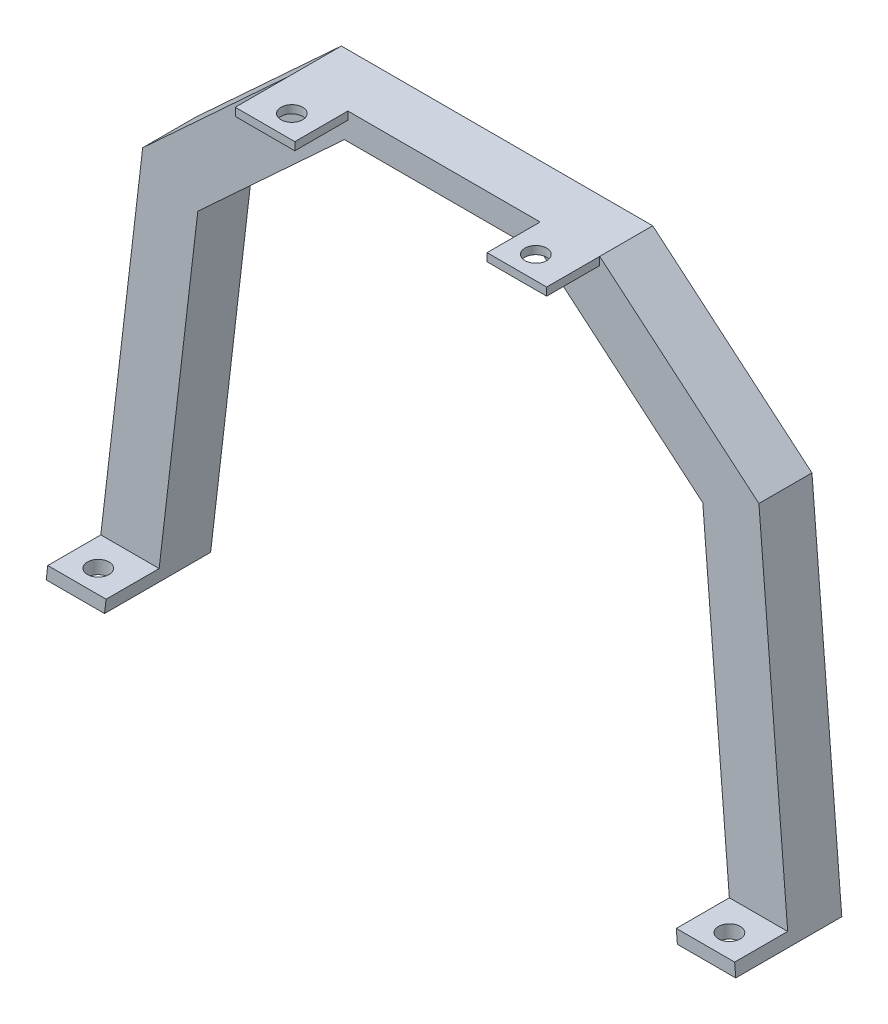
SolidWorks part; units mm, degrees
ref_plane "Front Plane" through (0, 0, 0) normal (0, 0, 1) x (1, 0, 0)
ref_plane "Top Plane" through (0, 0, 0) normal (0, 1, 0) x (1, 0, 0)
ref_plane "Right Plane" through (0, 0, 0) normal (1, 0, 0) x (0, 0, -1)
sketch "Sketch1" plane through (0, 0, 0) normal (0, 0, 1) x (1, 0, 0)
  line L0 (0, 0) -> (-11, 0)
  line L2 (108, 0) -> (119, 0)
  line L3 (-11, 0) -> (-2.811, 69.6627)
  line L16 (-2.811, 69.6627) -> (24.6463, 95)
  line L17 (24.6463, 95) -> (83.3537, 95)
  line L18 (83.3537, 95) -> (113.3741, 69.6627)
  line L19 (113.3741, 69.6627) -> (119, 0)
  line L20 (0, 0) -> (7.5811, 64.4912)
  line L21 (7.5811, 64.4912) -> (35.2243, 90)
  line L22 (35.2243, 90) -> (72.5681, 90)
  line L23 (72.5681, 90) -> (102.7918, 64.4912)
  line L24 (102.7918, 64.4912) -> (108, 0)
  point P1 (76.9939, 69.7206)
  point P3 (42.495, 69.6707)
  point P7 (0, 0)
  point P9 (0, 0)
  point P10 (4.4927, 54.3432)
  point P11 (0, 0)
  point P12 (29.0306, 74.7943)
  point P13 (1.953, 52.9858)
  point P14 (0, 0)
  point P15 (1.156, 51.9158)
  point P16 (110.4264, 51.9158)
  point P17 (110.0227, 51.9158)
  point P18 (-3.1434, 51.9158)
  point P25 (103.3774, 58.6554)
  point P26 (54, 95)
  point P27 (0, 0)
  point P29 (0, 0)
  point P30 (0, 0)
  point P31 (0, 0)
  point P32 (108, 69.1904)
  point P33 (98.6664, 62.6362)
  point P34 (81.8482, 93.6757)
  point P35 (76.1597, 90)
  point P36 (111.8984, 70.798)
  point P37 (-2.8611, 69.0667)
  point P38 (35.2271, 90)
  point P39 (72.2025, 90)
  point P40 (104.3549, 64.4912)
  point P41 (113.3823, 69.5614)
  dimension "D1" = 130
  dimension "D2" = 11
  dimension "D3" = 90
  dimension "D4" = 65
  dimension "D5" = 5
extrude "Boss-Extrude1" add sketch "Sketch1" along normal blind 10
sketch "Sketch2" plane through (0, 0, 10) normal (0, 0, 1) x (1, 0, 0)
  line L0 (-11, 0) -> (0, 0)
  line L1 (0, 0) -> (0.2939, 2.5)
  line L2 (0, 0) -> (7.5811, 64.4912) construction
  line L3 (0.2939, 2.5) -> (-10.7061, 2.5)
  line L4 (-2.811, 69.6627) -> (-11, 0) construction
  line L5 (-10.7061, 2.5) -> (-11, 0)
  line L6 (108, 0) -> (119, 0)
  line L7 (119, 0) -> (118.7981, 2.5)
  line L8 (119, 0) -> (113.3741, 69.6627) construction
  line L9 (118.7981, 2.5) -> (107.7981, 2.5)
  line L10 (102.7918, 64.4912) -> (108, 0) construction
  line L11 (107.7981, 2.5) -> (108, 0)
  point P14 (-5.5, 0)
  point P21 (113.5, 0)
  dimension "D1" = 2.5
  dimension "D2" = 2.5
extrude "Boss-Extrude2" add sketch "Sketch2" along normal blind 10
sketch "Sketch3" plane through (0, 2.5, 0) normal (0, 1, 0) x (1, 0, 0)
  line L0 (-11, -20) -> (-11, 0) construction
  line L1 (119, -20) -> (119, 0) construction
  circle A0 centre (-5.5, -15.6874) radius 2.05
  circle A1 centre (113.5, -15.6874) radius 2.05
  point P8 (0, 0)
  dimension "D3" = 4.1
  dimension "D1" = 5.5
  dimension "D2" = 5.5
extrude "Cut-Extrude1" cut sketch "Sketch3" against normal blind 10
sketch "Sketch4" plane through (0, 0, 10) normal (0, 0, 1) x (1, 0, 0)
  line L0 (-11, 0) -> (54, 0)
  line L1 (24.6463, 95) -> (35.8758, 95)
  line L2 (24.6463, 95) -> (24.6463, 93.5)
  line L3 (24.6463, 93.5) -> (35.8758, 93.5)
  line L4 (35.8758, 95) -> (35.8758, 93.5)
  line L9 (54, 0) -> (54, 79.0988)
  line L10 (72.1242, 95) -> (72.1242, 93.5)
  line L11 (83.3537, 93.5) -> (72.1242, 93.5)
  line L12 (83.3537, 95) -> (83.3537, 93.5)
  line L13 (83.3537, 95) -> (72.1242, 95)
  point P14 (70.1629, 71.8177)
  dimension "D1" = 1.5
  dimension "D2" = 65
extrude "Boss-Extrude3" add sketch "Sketch4" along normal blind 10 contours L3 L4 L1 L2 | L13 L10 L11 L12
sketch "Sketch6" plane through (0, 95, 0) normal (0, 1, 0) x (1, 0, 0)
  line L3 (54, -10) -> (54, 0)
  line L4 (72.1242, -10) -> (35.8758, -10) construction
  line L5 (83.3537, 0) -> (24.6463, 0) construction
  circle A0 centre (31, -15.6874) radius 2.05
  circle A1 centre (77, -15.6874) radius 2.05
  circle A7 centre (-5.5, -15.6874) radius 2.05
  point P2 (0, 0)
  point P12 (0, 0)
  point P13 (0, 0)
  point P14 (0, 0)
  dimension "D2" = 4.1
  dimension "D1" = 23
extrude "Cut-Extrude2" cut sketch "Sketch6" against normal blind 10 contours A0 | A1
